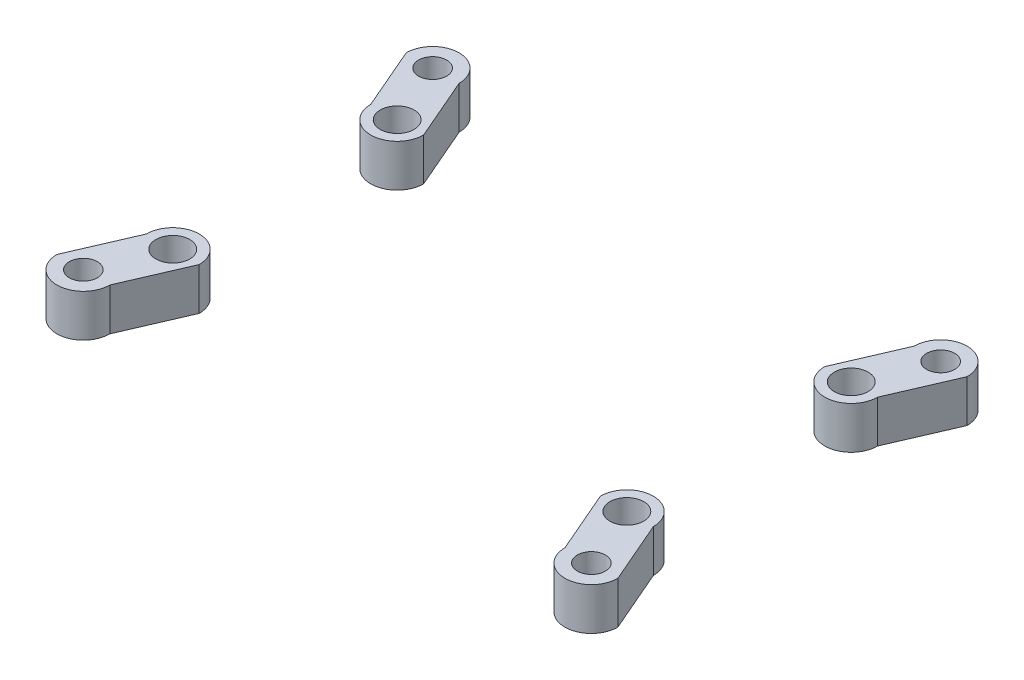
SolidWorks part; units mm, degrees
ref_plane "Front Plane" through (0, 0, 0) normal (0, 0, 1) x (1, 0, 0)
ref_plane "Top Plane" through (0, 0, 0) normal (0, 1, 0) x (1, 0, 0)
ref_plane "Right Plane" through (0, 0, 0) normal (1, 0, 0) x (0, 0, -1)
sketch "Sketch1" plane through (0, 0, 0) normal (0, 1, 0) x (1, 0, 0)
  line L0 (0, 16.5) -> (0, -16.5) construction
  line L1 (-24, -16.5) -> (24, -16.5) construction
  line L2 (-24, -16.5) -> (-24, 16.5) construction
  line L3 (-24, 16.5) -> (24, 16.5) construction
  line L4 (24, -16.5) -> (24, 16.5) construction
  line L5 (-24, -16.5) -> (24, 16.5) construction
  line L6 (-24, 16.5) -> (24, -16.5) construction
  line L7 (-24, 0) -> (24, 0) construction
  circle A0 centre (-24, 16.5) radius 1.325
  circle A1 centre (24, 16.5) radius 1.325
  circle A2 centre (-24, -16.5) radius 1.325
  circle A3 centre (24, -16.5) radius 1.325
  point P0 (0, 0)
  dimension "D3" = 2.65
  dimension "D1" = 48
  dimension "D2" = 33
sketch "Sketch4" plane through (0, 0, 0) normal (0, 1, 0) x (1, 0, 0)
  line L1 (-21.45, -10.6) -> (21.45, -10.6) construction
  line L2 (-21.45, -10.6) -> (-21.45, 10.6) construction
  line L3 (-21.45, 10.6) -> (21.45, 10.6) construction
  line L4 (21.45, -10.6) -> (21.45, 10.6) construction
  line L5 (-21.45, -10.6) -> (21.45, 10.6) construction
  line L6 (-21.45, 10.6) -> (21.45, -10.6) construction
  circle A0 centre (-21.45, 10.6) radius 1.6
  circle A1 centre (21.45, 10.6) radius 1.6
  circle A2 centre (-21.45, -10.6) radius 1.6
  circle A3 centre (21.45, -10.6) radius 1.6
  point P0 (0, 0)
  dimension "D3" = 3.2
  dimension "D1" = 42.9
  dimension "D2" = 21.2
sketch "Sketch5" plane through (0, 0, 0) normal (0, 1, 0) x (1, 0, 0)
  line L0 (-26.5, 16.5) -> (-23.95, 10.6)
  line L1 (-21.5, 16.5) -> (-18.95, 10.6)
  line L2 (0, 16.5) -> (0, -16.5) construction
  line L4 (21.5, 16.5) -> (18.95, 10.6)
  line L5 (26.5, 16.5) -> (23.95, 10.6)
  line L6 (-24, 0) -> (24, 0) construction
  line L7 (-24, -16.5) -> (-24, 16.5) construction
  line L8 (26.5, -16.5) -> (23.95, -10.6)
  line L9 (21.5, -16.5) -> (18.95, -10.6)
  line L10 (-21.5, -16.5) -> (-18.95, -10.6)
  line L11 (-26.5, -16.5) -> (-23.95, -10.6)
  arc A0 (-21.5, 16.5) -> (-26.5, 16.5) centre (-24, 16.5) ccw
  arc A1 (-23.95, 10.6) -> (-18.95, 10.6) centre (-21.45, 10.6) ccw
  arc A2 (23.95, 10.6) -> (18.95, 10.6) centre (21.45, 10.6) cw
  arc A3 (21.5, 16.5) -> (26.5, 16.5) centre (24, 16.5) cw
  arc A4 (21.5, -16.5) -> (26.5, -16.5) centre (24, -16.5) ccw
  arc A5 (23.95, -10.6) -> (18.95, -10.6) centre (21.45, -10.6) ccw
  arc A6 (-23.95, -10.6) -> (-18.95, -10.6) centre (-21.45, -10.6) cw
  arc A7 (-21.5, -16.5) -> (-26.5, -16.5) centre (-24, -16.5) cw
  dimension "D1" = 5
extrude "Boss-Extrude1" add sketch "Sketch5" along normal blind 4
extrude "Cut-Extrude1" cut sketch "Sketch1" along normal through all both and the other way through all
extrude "Cut-Extrude2" cut sketch "Sketch4" along normal through all both and the other way through all
